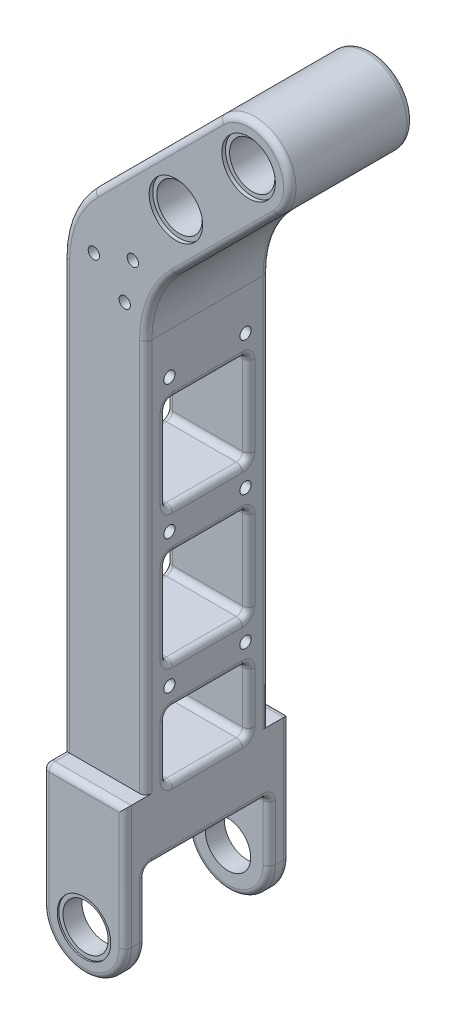
SolidWorks part; units mm, degrees
material "6061 合金"
ref_plane "前视基准面" through (0, 0, 0) normal (0, 0, 1) x (1, 0, 0)
ref_plane "上视基准面" through (0, 0, 0) normal (0, 1, 0) x (1, 0, 0)
ref_plane "右视基准面" through (0, 0, 0) normal (1, 0, 0) x (0, 0, -1)
other "Configuration Table"
sketch "草图1" plane through (0, 0, 0) normal (0, 0, 1) x (1, 0, 0)
  circle A0 centre (0, 0) radius 20
  circle A1 centre (0, 0) radius 11
  dimension "D1" = 40
  dimension "D2" = 22
extrude "凸台-拉伸1" add sketch "草图1" along normal blind 60 contours A1 | A0
ref_plane "基准面1" through (0, 0, 30) normal (0, 0, 1) x (1, 0, 0)
sketch "草图2" plane through (0, 0, 30) normal (0, 0, 1) x (1, 0, 0)
  line L0 (0, 0) -> (-70, -70) construction
  line L1 (-70, -70) -> (-70, -320) construction
  line L2 (0, -57.3148) -> (0, 49.9409) construction
  line L3 (-56.8582, 0) -> (46.4003, 0) construction
  line L4 (-14.1421, 14.1421) -> (-90, -61.7157)
  line L5 (14.1421, -14.1421) -> (-50, -78.2843)
  line L6 (-90, -61.7157) -> (-90, -320)
  line L7 (-50, -78.2843) -> (-50, -320)
  line L8 (-90, -320) -> (-50, -320)
  circle A2 centre (0, 0) radius 20 construction
  arc A3 (-14.1421, 14.1421) -> (14.1421, -14.1421) centre (0, 0) ccw
  dimension "D1" = 45
  dimension "D2" = 250
  dimension "D3" = 70
  dimension "D4" = 40
  dimension "D5" = 40
extrude "凸台-拉伸2" add sketch "草图2" along normal mid plane 60 contours L7 L8 L6 L4 A3 L5
sketch "草图4" plane through (0, 0, 60) normal (0, 0, 1) x (1, 0, 0)
  line L0 (-90, -61.7157) -> (-90, -320) construction
  line L1 (-90, -290) -> (-50, -290)
  line L2 (-90, -290) -> (-90, -350)
  line L4 (-50, -290) -> (-50, -350)
  line L5 (-50, -78.2843) -> (-50, -320) construction
  line L6 (-90, -320) -> (-50, -320) construction
  arc A0 (-90, -350) -> (-50, -350) centre (-70, -350) ccw
  circle A1 centre (-70, -350) radius 11
  dimension "D3" = 22
  dimension "D1" = 30
  dimension "D2" = 30
extrude "凸台-拉伸3" add sketch "草图4" along normal blind 10
mirror "镜向1" about plane through (0, 0, 30) normal (0, 0, 1) of "凸台-拉伸3"
sketch "草图5" plane through (0, 0, 0) normal (0, 1, 0) x (1, 0, 0)
  line L0 (0, 0) -> (0, -78.0582) construction
ref_plane "基准面2" through (-70, 0, 0) normal (-1, 0, 0) x (0, 0, 1)
sketch "草图7" plane through (-70, 0, 0) normal (-1, 0, 0) x (0, 0, 1)
  line L0 (-34.1239, -350) -> (109.535, -350) construction
sketch "草图8" plane through (0, 0, 60) normal (0, 0, 1) x (1, 0, 0)
  line L0 (0, 0) -> (-70, -70) construction
  circle A0 centre (-35.3553, -35.3553) radius 11
  dimension "D1" = 22
  dimension "D2" = 50
extrude "切除-拉伸1" cut sketch "草图8" against normal blind 100
fillet "圆角1" radius 50 2 edges at (-90, -61.7157, 30) (-50, -78.2843, 30)
fillet "圆角2" radius 3 34 edges at (-50, -320, 70) (-70, -370, 70) (-50, -335, 60) (-70, -370, 60) (-50, -335, 0) (-70, -370, 0) (-50, -320, -10) (-70, -370, -10) (-70, -320, 60) (-50, -320, 30) (-70, -320, 0) (-90, -290, 65) (-90, -320, 70) (-90, -335, 60) (-90, -320, 30) (-90, -335, 0) (-90, -320, -10) (-90, -290, -5) (-50, -194.4975, 0) (-46.194, -79.8608, 60) (-46.194, -79.8608, 0) (-10.6066, -38.8909, 0) (14.1421, 14.1421, 60) (14.1421, 14.1421, 0) (-44.7487, -16.4645, 0) (-86.194, -63.2922, 60) (-86.194, -63.2922, 0) (-90, -186.2132, 0) (-10.6066, -38.8909, 60) (-50, -194.4975, 60) (-90, -186.2132, 60) (-44.7487, -16.4645, 60) (-70, -290, 70) (-70, -290, -10)
sketch "草图9" plane through (0, 0, 70) normal (0, 0, 1) x (1, 0, 0)
  circle A0 centre (-70, -350) radius 13
  dimension "D1" = 26
extrude "切除-拉伸2" cut sketch "草图9" against normal blind 0.75
sketch "草图10" plane through (0, 0, -10) normal (0, 0, -1) x (-1, 0, 0)
  circle A0 centre (70, -350) radius 13
  dimension "D1" = 26
extrude "切除-拉伸3" cut sketch "草图10" against normal blind 0.75 contours A0
sketch "草图11" plane through (-90, 0, 0) normal (-1, 0, 0) x (0, 0, 1)
  circle A0 centre (48.5, -118.9949) radius 2.75
  circle A1 centre (48.5, -183.9949) radius 2.75
  circle A2 centre (48.5, -248.9949) radius 2.75
  circle A3 centre (11.5, -248.9949) radius 2.75
  circle A4 centre (11.5, -183.9949) radius 2.75
  circle A5 centre (11.5, -118.9949) radius 2.75
  dimension "D1" = 5.5
extrude "切除-拉伸4" cut sketch "草图11" against normal through all contours A1 | A2 | A0 | A3 | A4 | A5
sketch "草图12" plane through (-90, 0, 0) normal (-1, 0, 0) x (0, 0, 1)
  line L0 (30, -62.0134) -> (30, -339.6946) construction
  line L1 (10, -128.9949) -> (50, -128.9949)
  line L2 (10, -128.9949) -> (10, -173.9949)
  line L3 (10, -173.9949) -> (50, -173.9949)
  line L4 (50, -128.9949) -> (50, -173.9949)
  line L5 (10, -193.9949) -> (50, -193.9949)
  line L6 (10, -193.9949) -> (10, -238.9949)
  line L7 (10, -238.9949) -> (50, -238.9949)
  line L8 (50, -193.9949) -> (50, -238.9949)
  line L9 (10, -258.9949) -> (50, -258.9949)
  line L10 (10, -258.9949) -> (10, -290)
  line L11 (10, -290) -> (50, -290)
  line L12 (50, -258.9949) -> (50, -290)
  line L13 (19.5, -173.9949) -> (40.5, -173.9949)
  line L14 (19.5, -173.9949) -> (19.5, -193.9949)
  line L15 (19.5, -193.9949) -> (40.5, -193.9949)
  line L16 (40.5, -173.9949) -> (40.5, -193.9949)
  line L17 (19.5, -238.9949) -> (40.5, -238.9949)
  line L18 (19.5, -238.9949) -> (19.5, -258.9949)
  line L19 (19.5, -258.9949) -> (40.5, -258.9949)
  line L20 (40.5, -238.9949) -> (40.5, -258.9949)
  line L21 (60, -82.4264) -> (60, -290) construction
  line L22 (0, -290) -> (0, -82.4264) construction
  line L23 (57, -320) -> (3, -320) construction
  circle A0 centre (48.5, -118.9949) radius 2.75 construction
  circle A1 centre (48.5, -183.9949) radius 2.75 construction
  circle A2 centre (48.5, -248.9949) radius 2.75 construction
  dimension "D1" = 10
  dimension "D2" = 10
  dimension "D3" = 10
  dimension "D4" = 8
  dimension "D5" = 10
  dimension "D6" = 10
  dimension "D7" = 10
  dimension "D8" = 30
extrude "减重" cut sketch "草图12" against normal through all contours L0 L1 L2 L3 | L15 L0 L17 L7 L8 L5 | L0 L5 L6 L7 | L19 L0 L11 L12 L9 | L0 L9 L10 L11 | L1 L0 L13 L3 L4
fillet "圆角3" radius 3 36 edges at (-90, -258.9949, 30) (-50, -258.9949, 30) (-50, -290, 30) (-90, -290, 30) (-50, -238.9949, 30) (-50, -193.9949, 30) (-90, -193.9949, 30) (-90, -238.9949, 30) (-50, -173.9949, 30) (-90, -173.9949, 30) (-50, -128.9949, 30) (-90, -128.9949, 30) (-70, -290, 10) (-90, -274.4975, 10) (-70, -258.9949, 10) (-50, -274.4975, 10) (-50, -274.4975, 50) (-70, -258.9949, 50) (-90, -274.4975, 50) (-70, -290, 50) (-50, -216.4949, 50) (-70, -193.9949, 50) (-90, -216.4949, 50) (-70, -238.9949, 50) (-70, -238.9949, 10) (-90, -216.4949, 10) (-70, -193.9949, 10) (-50, -216.4949, 10) (-70, -173.9949, 10) (-90, -151.4949, 10) (-70, -128.9949, 10) (-50, -151.4949, 10) (-50, -151.4949, 50) (-70, -128.9949, 50) (-90, -151.4949, 50) (-70, -173.9949, 50)
sketch "草图13" plane through (0, 0, 60) normal (0, 0, 1) x (1, 0, 0)
  circle A0 centre (0, 0) radius 13
  circle A1 centre (-35.3553, -35.3553) radius 13
  dimension "D1" = 26
  dimension "D2" = 26
extrude "切除-拉伸6" cut sketch "草图13" against normal blind 1.75
sketch "草图14" plane through (0, 0, 0) normal (0, 0, -1) x (-1, 0, 0)
  circle A0 centre (0, 0) radius 13
  circle A1 centre (35.3553, -35.3553) radius 13
  dimension "D1" = 26
  dimension "D2" = 26
extrude "切除-拉伸7" cut sketch "草图14" against normal blind 1.75
sketch "草图15" plane through (0, 0, 0) normal (0, 0, -1) x (-1, 0, 0)
  line L0 (0, 0) -> (70, -350) construction
  line L1 (56.2719, -67.2005) -> (60.1942, -86.8121) construction
  line L2 (70, -350) -> (204.3541, -323.1292) construction
  circle A0 centre (56.2719, -67.2005) radius 2.75
  circle A1 centre (75.2172, -73.6095) radius 2.75
  circle A2 centre (60.1942, -86.8121) radius 2.75
  dimension "D1" = 5.5
  dimension "D2" = 20
  dimension "D3" = 20
  dimension "D4" = 20
  dimension "D5" = 42
  dimension "D6" = 270
extrude "切除-拉伸8" cut sketch "草图15" against normal through all contours A2 | A0 | A1
ref_plane "小腿主干连杆面" through (0, 0, 0) normal (0.9806, -0.1961, 0) x (0, 0, -1)
ref_plane "小腿主干对称面" through (0, 0, 30) normal (0, 0, -1) x (-1, 0, 0)
